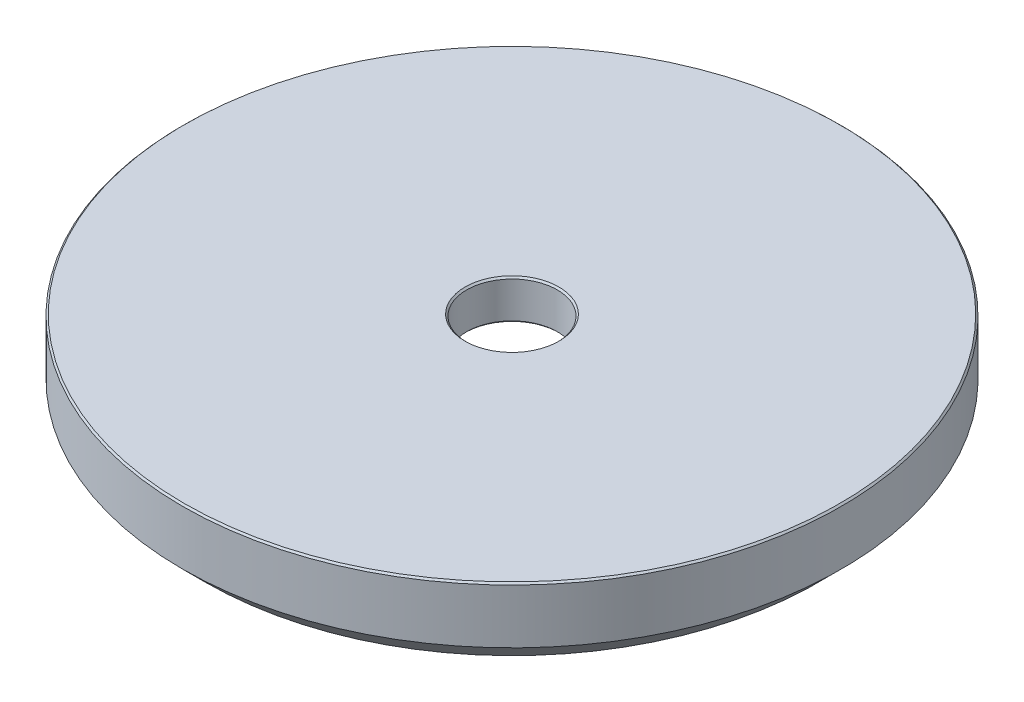
SolidWorks part; units mm, degrees
ref_plane "前基準面" through (0, 0, 0) normal (0, 0, 1) x (1, 0, 0)
ref_plane "上基準面" through (0, 0, 0) normal (0, 1, 0) x (1, 0, 0)
ref_plane "右基準面" through (0, 0, 0) normal (1, 0, 0) x (0, 0, -1)
sketch "草圖1" plane through (0, 0, 0) normal (0, 0, 1) x (1, 0, 0)
  line L0 (200, 58) -> (0, 58)
  line L1 (0, 58) -> (0, 10)
  line L2 (0, 10) -> (200, 10)
  line L3 (200, 10) -> (200, 58)
  line L4 (0, 58) -> (0, 10) construction
revolve "旋轉1" add sketch "草圖1" angle 360 about L4
hole_wizard "鑽孔1" positions "草圖3" profile "草圖2" legacy
sketch "草圖3" plane through (0, 10, 0) normal (0, -1, 0) x (-1, 0, 0)
  point P0 (0, 0)
sketch "草圖2" plane through (0, 10, 0) normal (1, 0, 0) x (0, 0, -1)
  line L0 (0, 0) -> (0, 15)
  line L1 (0, 15) -> (143, 15)
  line L2 (143, 15) -> (143, 0)
  line L3 (143, 0) -> (0, 0)
  line L4 (0, 110) -> (0, -10) construction
  dimension "直徑" = 286
  dimension "深度" = 15
sketch "草圖4" plane through (0, 0, 0) normal (0, 0, 1) x (1, 0, 0)
  line L0 (134, 25) -> (0, 25)
  line L1 (0, 25) -> (0, 15)
  line L2 (0, 15) -> (134, 15)
  line L3 (134, 15) -> (134, 25)
  line L4 (0, 25) -> (0, 15) construction
revolve "旋轉2" add sketch "草圖4" angle 360 about L4
sketch "草圖5" plane through (0, 0, 0) normal (0, 0, 1) x (1, 0, 0)
  line L0 (143, 10) -> (150, 10)
  line L1 (150, 10) -> (150, 18)
  line L2 (150, 18) -> (143, 18)
  line L3 (143, 18) -> (143, 10)
  line L4 (0, 18) -> (0, 10) construction
revolve "除料-旋轉1" cut sketch "草圖5" angle 360 about L4
hole_wizard "鑽孔3" positions "草圖9" profile "草圖8" legacy
sketch "草圖9" plane through (0, 15, 0) normal (0, -1, 0) x (-1, 0, 0)
  point P0 (0, 0)
sketch "草圖8" plane through (0, 15, 0) normal (1, 0, 0) x (0, 0, -1)
  line L0 (0, 0) -> (0, 43)
  line L1 (0, 43) -> (27.5, 43)
  line L2 (27.5, 43) -> (27.5, 19)
  line L3 (27.5, 19) -> (62.5, 19)
  line L4 (62.5, 19) -> (62.5, 0)
  line L5 (62.5, 0) -> (0, 0)
  line L6 (0, 110) -> (0, -10) construction
  dimension "直徑" = 55
  dimension "深度" = 43
  dimension "柱孔直徑1" = 125
  dimension "柱孔深度1" = 19
chamfer "導角1" distance 1 angle 45 4 edges at (0, 58, -200) (0, 58, -27.5) (0, 34, -27.5) (0, 15, -62.5)
chamfer "導角2" distance 3 angle 45 1 edges at (0, 10, -150)
chamfer "導角3" distance 14 angle 45 1 edges at (0, 10, -200)
chamfer "導角4" distance 2 angle 45 1 edges at (0, 18, -143)
